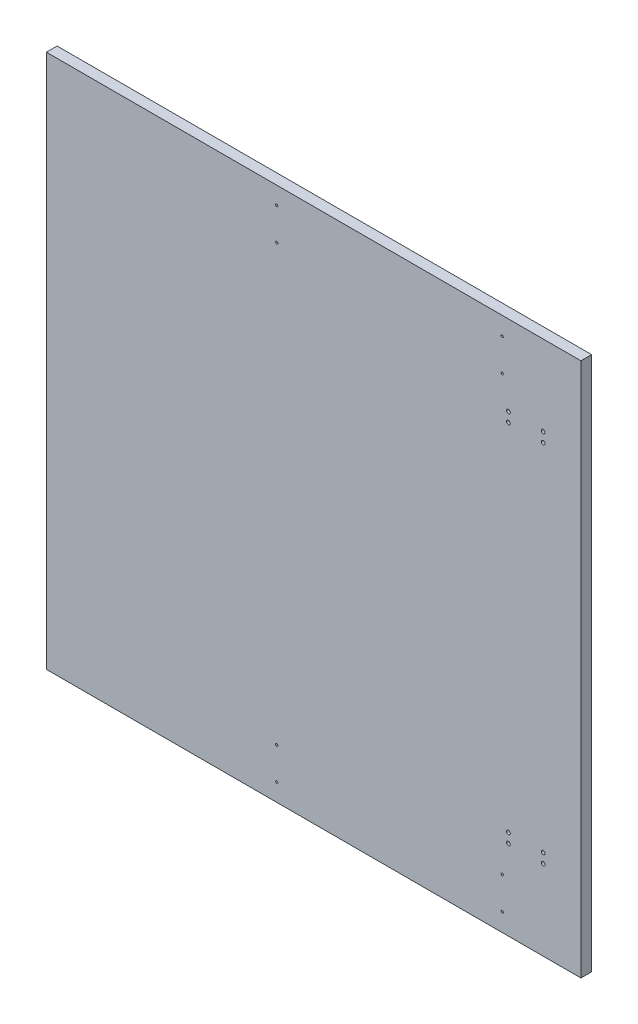
SolidWorks part; units mm, degrees
ref_plane "Front Plane" through (0, 0, 0) normal (0, 0, 1) x (1, 0, 0)
ref_plane "Top Plane" through (0, 0, 0) normal (0, 1, 0) x (1, 0, 0)
ref_plane "Right Plane" through (0, 0, 0) normal (1, 0, 0) x (0, 0, -1)
sketch "Sketch5" plane through (0, 0, 0) normal (0, 0, 1) x (1, 0, 0)
  line L1 (-500, -500) -> (500, -500)
  line L2 (-500, -500) -> (-500, 500)
  line L3 (-500, 500) -> (500, 500)
  line L4 (500, -500) -> (500, 500)
  line L5 (-500, -500) -> (500, 500) construction
  line L6 (-500, 500) -> (500, -500) construction
  point P0 (0, 0)
  dimension "D1" = 1000
extrude "Boss-Extrude1" add sketch "Sketch5" along normal blind 20
sketch "Sketch6" plane through (0, 0, 20) normal (0, 0, 1) x (1, 0, 0)
  line L0 (0, 0) -> (0, 108.6071) construction
  line L1 (-396.85, 420) -> (396.85, 420) construction
  line L2 (-396.85, 420) -> (-396.85, 390) construction
  line L3 (-396.85, 390) -> (396.85, 390) construction
  line L4 (396.85, 420) -> (396.85, 390) construction
  line L5 (-396.85, 420) -> (396.85, 390) construction
  line L6 (-396.85, 390) -> (396.85, 420) construction
  line L7 (-396.85, 388) -> (396.85, 388) construction
  line L8 (-396.85, 388) -> (-396.85, 358) construction
  line L9 (-396.85, 358) -> (396.85, 358) construction
  line L10 (396.85, 388) -> (396.85, 358) construction
  line L11 (-396.85, 388) -> (396.85, 358) construction
  line L12 (-396.85, 358) -> (396.85, 388) construction
  line L13 (396.85, 356) -> (396.85, 326) construction
  line L14 (364.35, 356) -> (429.35, 356) construction
  line L15 (364.35, 356) -> (364.35, 326) construction
  line L16 (364.35, 326) -> (429.35, 326) construction
  line L17 (429.35, 356) -> (429.35, 326) construction
  line L18 (364.35, 356) -> (429.35, 326) construction
  line L19 (364.35, 326) -> (429.35, 356) construction
  line L20 (364.35, 341) -> (429.35, 341) construction
  line L21 (500, 500) -> (-500, 500) construction
  line L22 (355.979, 461.4) -> (349.629, 461.4) construction
  line L23 (-132.27, 405) -> (-62.74, 405) construction
  line L24 (-62.74, 420) -> (-62.74, 390) construction
  line L25 (346.454, 420) -> (346.454, 390) construction
  line L26 (-62.74, 405) -> (346.454, 405) construction
  line L27 (-132.27, 420) -> (-132.27, 390) construction
  line L28 (-65.915, 462.4) -> (-72.265, 462.4) construction
  line L29 (-65.915, 462.4) -> (-65.915, 411.6) construction
  line L30 (-65.915, 411.6) -> (-72.265, 411.6) construction
  line L31 (-72.265, 462.4) -> (-72.265, 411.6) construction
  line L32 (-65.915, 462.4) -> (-72.265, 411.6) construction
  line L33 (-65.915, 411.6) -> (-72.265, 462.4) construction
  line L34 (-75.44, 406.8375) -> (-62.74, 406.8375) construction
  line L35 (-75.44, 406.8375) -> (-75.44, 467.1625) construction
  line L36 (-75.44, 467.1625) -> (-62.74, 467.1625) construction
  line L37 (-62.74, 406.8375) -> (-62.74, 467.1625) construction
  line L38 (-75.44, 406.8375) -> (-62.74, 467.1625) construction
  line L39 (-75.44, 467.1625) -> (-62.74, 406.8375) construction
  line L40 (355.979, 461.4) -> (355.979, 410.6) construction
  line L41 (355.979, 410.6) -> (349.629, 410.6) construction
  line L42 (349.629, 461.4) -> (349.629, 410.6) construction
  line L43 (355.979, 461.4) -> (349.629, 410.6) construction
  line L44 (355.979, 410.6) -> (349.629, 461.4) construction
  line L45 (346.454, 405.8375) -> (359.154, 405.8375) construction
  line L46 (346.454, 405.8375) -> (346.454, 466.1625) construction
  line L47 (346.454, 466.1625) -> (359.154, 466.1625) construction
  line L48 (359.154, 405.8375) -> (359.154, 466.1625) construction
  line L49 (346.454, 405.8375) -> (359.154, 466.1625) construction
  line L50 (346.454, 466.1625) -> (359.154, 405.8375) construction
  line L51 (-132.27, 388) -> (-132.27, 358) construction
  line L52 (-62.74, 388) -> (-62.74, 358) construction
  line L53 (346.454, 388) -> (346.454, 358) construction
  line L54 (-132.27, 421) -> (-132.27, 451) construction
  line L55 (-62.74, 421) -> (-62.74, 451) construction
  line L56 (346.454, 421) -> (346.454, 451) construction
  line L57 (-396.85, 452) -> (-75.44, 452) construction
  line L58 (-396.85, 452) -> (-396.85, 422) construction
  line L59 (-396.85, 422) -> (-75.44, 422) construction
  line L60 (-396.85, 437) -> (-75.44, 437) construction
  point P0 (0, 405)
  point P5 (0, 373)
  point P12 (396.85, 341)
  point P13 (352.804, 405.8375)
  point P19 (364.35, 350)
  point P20 (364.35, 332)
  point P21 (429.35, 332)
  point P22 (429.35, 350)
  point P30 (-69.09, 437)
  point P42 (-69.09, 437)
  point P48 (-69.09, 467.1625)
  point P50 (352.804, 436)
  point P54 (352.804, 436)
  point P60 (352.804, 466.1625)
  point P61 (346.454, 436)
  point P64 (-62.74, 436)
  point P65 (-62.74, 373)
  point P66 (-69.09, 406.8375)
  point P71 (346.454, 373)
  point P78 (346.454, 436)
  point P82 (-204.5703, 458.9268)
  point P83 (-62.74, 436)
  point P84 (-62.74, 437)
  point P87 (-396.85, 458.5906)
  dimension "D1" = 2
  dimension "D2" = 30
  dimension "D3" = 793.7
  dimension "D4" = 30
  dimension "D5" = 65
  dimension "D6" = 18
  dimension "D7" = 2
  dimension "D8" = 80
  dimension "D9" = 409.194
  dimension "D10" = 69.53
  dimension "D11" = 529.12
  dimension "D12" = 12.7
  dimension "D13" = 6.35
  dimension "D14" = 60.325
  dimension "D15" = 50.8
  dimension "D16" = 2
  dimension "D17" = 30
  dimension "D18" = 2
hole_wizard "M8x1.0 Tapped Hole1" positions "3DSketch1" profile "Sketch7" tap size "M8x1.0" standard "ANSI Metric" end condition through all
sketch3d "3DSketch1"
  point P0 (364.35, 350, 20)
  point P3 (364.35, 332, 20)
  point P6 (429.35, 332, 20)
  point P9 (429.35, 350, 20)
sketch "Sketch7" plane through (364.35, 350, 20) normal (1, 0, 0) x (0, -1, 0)
  line L0 (0, 0) -> (0, 20)
  line L1 (0, 20) -> (3.5, 20)
  line L2 (3.5, 20) -> (3.5, 0)
  line L5 (3.5, 0) -> (0, 0)
  line L11 (0, -6.35) -> (0, 107.95) construction
  dimension "Thru Tap Drill Dia." = 7
  dimension "Thru Tap Drill Depth" = 20
cosmetic thread "Hole Thread1" parameters "D2"=8
cosmetic thread "Hole Thread2" parameters "D2"=8
cosmetic thread "Hole Thread3" parameters "D2"=8
cosmetic thread "Hole Thread4" parameters "D2"=8
hole_wizard "M5x0.8 Tapped Hole1" positions "3DSketch3" profile "Sketch9" tap size "M5x0.8" standard "ANSI Metric" end condition through all
sketch3d "3DSketch3"
  point P0 (-69.09, 406.8375, 20)
  point P3 (-69.09, 467.1625, 20)
  point P6 (352.804, 466.1625, 20)
  point P9 (352.804, 405.8375, 20)
sketch "Sketch9" plane through (-69.09, 406.8375, 20) normal (1, 0, 0) x (0, -1, 0)
  line L0 (0, 0) -> (0, 20)
  line L1 (0, 20) -> (2.1, 20)
  line L2 (2.1, 20) -> (2.1, 0)
  line L5 (2.1, 0) -> (0, 0)
  line L11 (0, -6.35) -> (0, 107.95) construction
  dimension "Thru Tap Drill Dia." = 4.2
  dimension "Thru Tap Drill Depth" = 20
cosmetic thread "Hole Thread5" parameters "D2"=5
cosmetic thread "Hole Thread6" parameters "D2"=5
cosmetic thread "Hole Thread7" parameters "D2"=5
cosmetic thread "Hole Thread8" parameters "D2"=5
mirror "Mirror1" about plane through (0, 0, 0) normal (0, 1, 0) of "M5x0.8 Tapped Hole1", "M8x1.0 Tapped Hole1"
cosmetic thread "Hole Thread9" parameters "D2"=8
cosmetic thread "Hole Thread10" parameters "D2"=5
cosmetic thread "Hole Thread11" parameters "D2"=5
cosmetic thread "Hole Thread12" parameters "D2"=8
cosmetic thread "Hole Thread13" parameters "D2"=8
cosmetic thread "Hole Thread14" parameters "D2"=5
cosmetic thread "Hole Thread15" parameters "D2"=5
cosmetic thread "Hole Thread16" parameters "D2"=8
